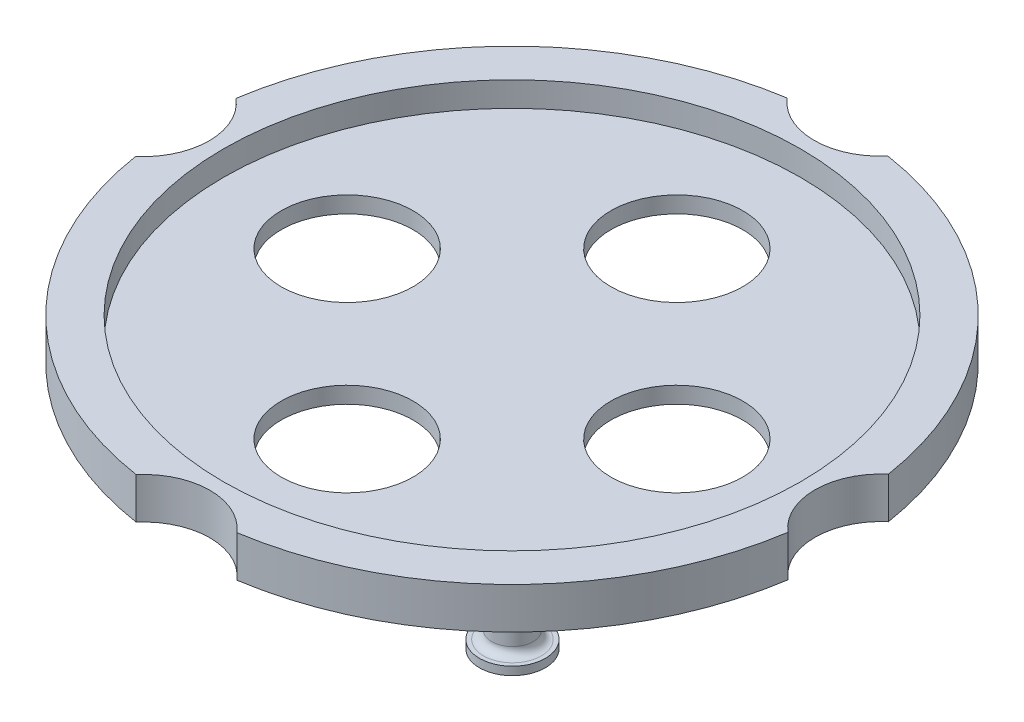
SolidWorks part; units mm, degrees
ref_plane "Front Plane" through (0, 0, 0) normal (0, 0, 1) x (1, 0, 0)
ref_plane "Top Plane" through (0, 0, 0) normal (0, 1, 0) x (1, 0, 0)
ref_plane "Right Plane" through (0, 0, 0) normal (1, 0, 0) x (0, 0, -1)
sketch "Sketch1" plane through (0, 0, 0) normal (0, 1, 0) x (1, 0, 0)
  circle A0 centre (0, 0) radius 50.8
  dimension "5" = 101.6
extrude "Boss-Extrude1" add sketch "Sketch1" along normal blind 6.35
sketch "Sketch2" plane through (0, 6.35, 0) normal (0, 1, 0) x (1, 0, 0)
  circle A0 centre (0, 0) radius 44.45
  dimension "D1" = 88.9
extrude "Cut-Extrude1" cut sketch "Sketch2" against normal blind 3.81
sketch "Sketch3" plane through (0, 6.35, 0) normal (0, 1, 0) x (1, 0, 0)
  line L0 (-50.8, 0) -> (50.8, 0) construction
  line L1 (75.6687, 0) -> (87.8373, 0) construction
  circle A0 centre (0, 0) radius 50.8 construction
  arc A1 (50.1973, 7.8021) -> (50.2142, -7.6927) centre (56.7786, 0.0618) ccw
  arc A2 (50.2142, -7.6927) -> (50.1973, 7.8021) centre (0, 0) ccw
  arc A3 (-7.6927, -50.2142) -> (7.8021, -50.1973) centre (0, 0) ccw
  arc A4 (7.8021, -50.1973) -> (-7.6927, -50.2142) centre (0.0618, -56.7786) ccw
  arc A5 (-50.2142, 7.6927) -> (-50.1973, -7.8021) centre (0, 0) ccw
  arc A6 (-50.1973, -7.8021) -> (-50.2142, 7.6927) centre (-56.7786, -0.0618) ccw
  arc A7 (7.6927, 50.2142) -> (-7.8021, 50.1973) centre (0, 0) ccw
  arc A8 (-7.8021, 50.1973) -> (7.6927, 50.2142) centre (-0.0618, 56.7786) ccw
  circle A9 centre (-25.4, 0) radius 10.16
  circle A10 centre (0, 25.4) radius 10.16
  circle A11 centre (25.4, 0) radius 10.16
  circle A12 centre (0, -25.4) radius 10.16
  point P23 (0, 0)
  point P33 (0, 0)
  dimension "D1" = 10.16
  dimension "D3" = 20.32
  dimension "D4" = 25.4
  dimension "D2" = 4
  dimension "D5" = 4
extrude "Cut-Extrude2" cut sketch "Sketch3" against normal through all
sketch "Sketch5" plane through (0, 0, 0) normal (0, -1, 0) x (1, 0, 0)
  line L0 (0, 0) -> (-35.8819, 35.9601) construction
  arc A0 (-7.6927, 50.2142) -> (-50.1973, 7.8021) centre (0, 0) ccw construction
  circle A1 centre (-30.4996, 30.5661) radius 3.175
  dimension "D1" = 6.35
  dimension "D2" = 43.18
extrude "Boss-Extrude3" add sketch "Sketch5" along normal blind 6.35 contours A1
sketch "Sketch6" plane through (0, -6.35, 0) normal (0, -1, 0) x (1, 0, 0)
  circle A0 centre (-30.4996, 30.5661) radius 5.08
  dimension "D1" = 10.16
extrude "Boss-Extrude4" add sketch "Sketch6" along normal blind 1.27
fillet "Fillet1" radius 1.27 2 edges at (-30.4996, -6.35, 27.3911) (-30.4996, 0, 33.7411)
pattern_circular "CirPattern1" count 4 over 360 about axis through (0, 0, 0) along (0, 1, 0) of "Fillet1", "Boss-Extrude3", "Boss-Extrude4"
